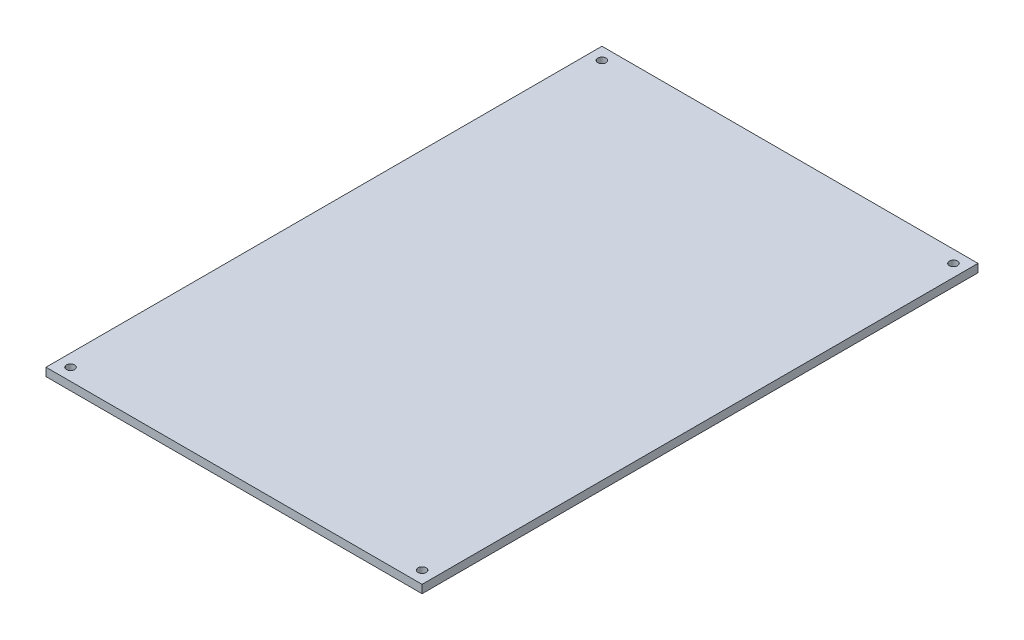
SolidWorks part; units mm, degrees
ref_plane "Front Plane" through (0, 0, 0) normal (0, 0, 1) x (1, 0, 0)
ref_plane "Top Plane" through (0, 0, 0) normal (0, 1, 0) x (1, 0, 0)
ref_plane "Right Plane" through (0, 0, 0) normal (1, 0, 0) x (0, 0, -1)
sketch "Sketch1" plane through (0, 0, 0) normal (0, 1, 0) x (1, 0, 0)
  line L0 (-136.525, -206.375) -> (-136.525, 206.375) construction
  line L1 (-146.05, -215.9) -> (146.05, -215.9)
  line L2 (-146.05, -215.9) -> (-146.05, 215.9)
  line L3 (-146.05, 215.9) -> (146.05, 215.9)
  line L4 (146.05, -215.9) -> (146.05, 215.9)
  line L5 (-146.05, -215.9) -> (146.05, 215.9) construction
  line L6 (-146.05, 215.9) -> (146.05, -215.9) construction
  line L7 (-136.525, 206.375) -> (136.525, 206.375) construction
  line L8 (136.525, -206.375) -> (136.525, 206.375) construction
  line L9 (-136.525, -206.375) -> (136.525, -206.375) construction
  circle A0 centre (-136.525, 206.375) radius 3.1826
  circle A1 centre (136.525, 206.375) radius 3.1826
  circle A2 centre (136.525, -206.375) radius 3.1826
  circle A3 centre (-136.525, -206.375) radius 3.1826
  point P0 (0, 0)
  dimension "D4" = 6.3652
  dimension "D1" = 292.1
  dimension "D2" = 431.8
  dimension "D3" = 9.525
extrude "Boss-Extrude1" add sketch "Sketch1" along normal blind 6.35
